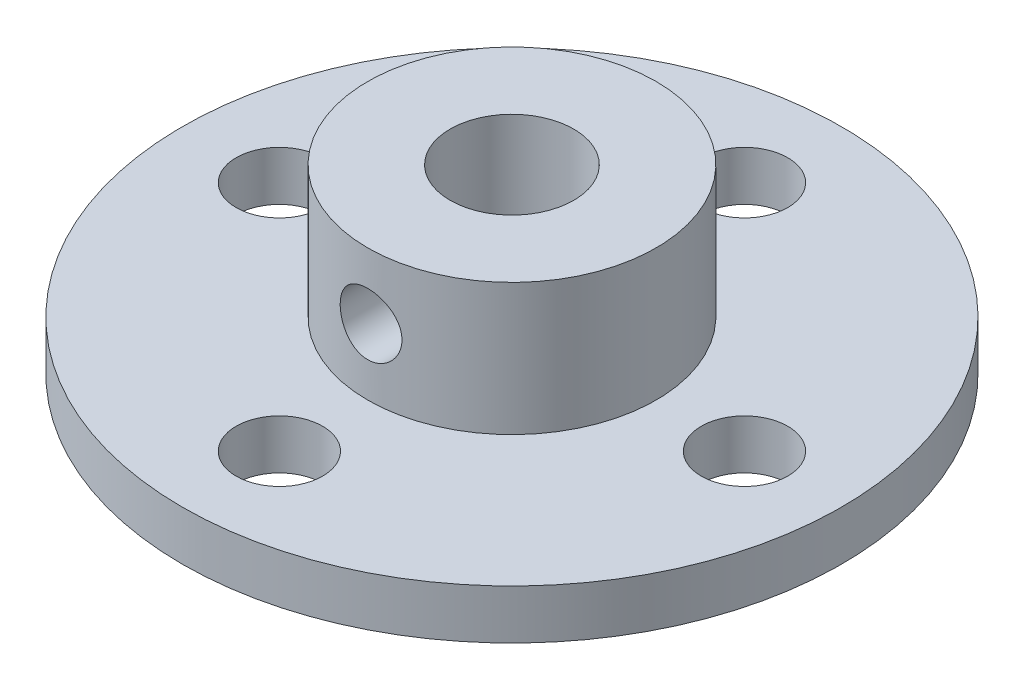
SolidWorks part; units mm, degrees
ref_plane "前基準面" through (0, 0, 0) normal (0, 0, 1) x (1, 0, 0)
ref_plane "上基準面" through (0, 0, 0) normal (0, 1, 0) x (1, 0, 0)
ref_plane "右基準面" through (0, 0, 0) normal (1, 0, 0) x (0, 0, -1)
sketch "草圖1" plane through (0, 0, 0) normal (0, 1, 0) x (1, 0, 0)
  circle A0 centre (0, 0) radius 16
  dimension "D1" = 32
extrude "填料-伸長1" add sketch "草圖1" along normal blind 2.4
sketch "草圖2" plane through (0, 2.4, 0) normal (0, 1, 0) x (1, 0, 0)
  circle A0 centre (0, 0) radius 7
  dimension "D1" = 14
extrude "填料-伸長2" add sketch "草圖2" along normal blind 6.4
sketch "草圖3" plane through (0, 8.8, 0) normal (0, 1, 0) x (1, 0, 0)
  circle A0 centre (0, 0) radius 3
  dimension "D1" = 6
extrude "除料-伸長1" cut sketch "草圖3" against normal up to next
sketch "草圖4" plane through (0, 2.4, 0) normal (0, 1, 0) x (1, 0, 0)
  circle A0 centre (0, 11.29) radius 2.1
  circle A1 centre (11.29, 0) radius 2.1
  circle A2 centre (0, -11.29) radius 2.1
  circle A3 centre (-11.29, 0) radius 2.1
  point P12 (0, 0)
  dimension "D1" = 4.2
  dimension "D2" = 11.29
  dimension "D3" = 4
extrude "除料-伸長2" cut sketch "草圖4" against normal up to next
sketch "草圖5" plane through (0, 0, 0) normal (0, 0, 1) x (1, 0, 0)
  line L0 (-7, 8.8) -> (-7, 2.4) construction
  line L1 (7, 8.8) -> (-7, 8.8) construction
  circle A0 centre (0, 5.6) radius 1.5
  dimension "D1" = 3
  dimension "D2" = 7
  dimension "D3" = 3.2
extrude "除料-伸長3" cut sketch "草圖5" along normal up to next
